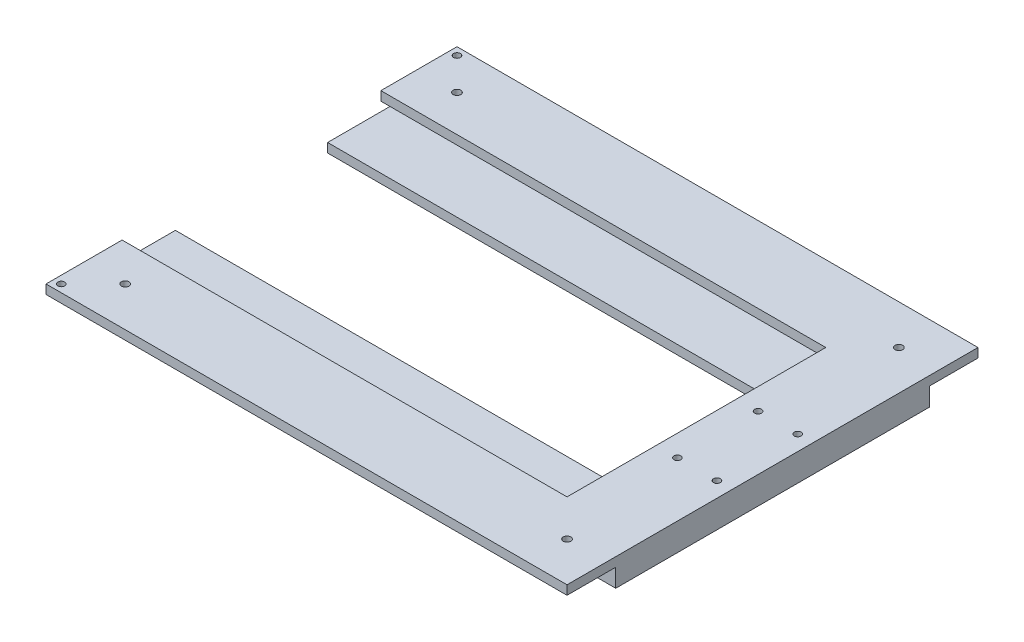
SolidWorks part; units mm, degrees
ref_plane "Спереди" through (0, 0, 0) normal (0, 0, 1) x (1, 0, 0)
ref_plane "Сверху" through (0, 0, 0) normal (0, 1, 0) x (1, 0, 0)
ref_plane "Справа" through (0, 0, 0) normal (1, 0, 0) x (0, 0, -1)
sketch "Эскиз1" plane through (0, 0, 0) normal (0, 1, 0) x (1, 0, 0)
  line L0 (50, -77.9215) -> (50, -347.9215)
  line L1 (-292.3, -77.9215) -> (50, -77.9215)
  line L2 (-292.3, -77.9215) -> (-292.3, -127.9215)
  line L3 (-292.3, -347.9215) -> (50, -347.9215)
  line L5 (-292.3, -127.9215) -> (0, -127.9215)
  line L7 (-292.3, -297.9215) -> (0, -297.9215)
  line L13 (-292.3, -297.9215) -> (-292.3, -347.9215)
  line L22 (0, -127.9215) -> (0, -297.9215)
  dimension "D1" = 342.3
  dimension "D12" = 50
  dimension "D2" = 270
  dimension "D3" = 50
  dimension "D4" = 50
  dimension "D9" = 50
  dimension "D8" = 77.9215
extrude "Бобышка-Вытянуть2" add sketch "Эскиз1" along normal blind 6
sketch "Эскиз2" plane through (0, 0, 0) normal (0, -1, 0) x (1, 0, 0)
  line L0 (-292.3, 127.9215) -> (0, 127.9215) construction
  line L5 (50, 347.9215) -> (50, 77.9215) construction
  line L6 (0, 297.9215) -> (-292.3, 297.9215) construction
  line L18 (50, 315.9215) -> (50, 109.9215)
  line L20 (6, 303.9215) -> (6, 121.9215)
  line L21 (-292.3, 77.9215) -> (-292.3, 127.9215) construction
  line L22 (50, 109.9215) -> (-292.3, 109.9215)
  line L24 (6, 121.9215) -> (-292.3, 121.9215)
  line L25 (-292.3, 109.9215) -> (-292.3, 121.9215)
  line L26 (-292.3, 297.9215) -> (-292.3, 347.9215) construction
  line L27 (50, 315.9215) -> (-292.3, 315.9215)
  line L29 (6, 303.9215) -> (-292.3, 303.9215)
  line L30 (-292.3, 315.9215) -> (-292.3, 303.9215)
  dimension "D1" = 44
  dimension "D2" = 12
  dimension "D3" = 12
  dimension "D4" = 6
  dimension "D5" = 6
extrude "Бобышка-Вытянуть3" add sketch "Эскиз2" along normal blind 6
sketch "Эскиз4" plane through (0, 6, 0) normal (0, 1, 0) x (1, 0, 0)
  line L0 (50, -77.9215) -> (-292.3, -77.9215) construction
  line L1 (-292.3, -77.9215) -> (-292.3, -127.9215) construction
  circle A0 centre (-266.3, -103.9215) radius 2.5
  dimension "D1" = 5
  dimension "D2" = 26
  dimension "D3" = 26
extrude "Вырез-Вытянуть1" cut sketch "Эскиз4" against normal through all
pattern_linear "Линейный массив2" count 2 spacing 290.3 along (1, 0, 0) count 2 spacing 218 along (0, 0, 1) of "Вырез-Вытянуть1"
sketch "Эскиз5" plane through (0, -6, 0) normal (0, -1, 0) x (1, 0, 0)
  line L8 (50, 315.9215) -> (-292.3, 315.9215)
  line L9 (-292.3, 315.9215) -> (-292.3, 262.9215)
  line L10 (-292.3, 262.9215) -> (0, 262.9215)
  line L11 (0, 262.9215) -> (0, 162.9215)
  line L12 (0, 162.9215) -> (-292.3, 162.9215)
  line L13 (-292.3, 162.9215) -> (-292.3, 109.9215)
  line L14 (-292.3, 109.9215) -> (50, 109.9215)
  line L15 (50, 109.9215) -> (50, 315.9215)
  point P0 (0, 212.9215)
  point P9 (50, 212.9215)
  dimension "D1" = 100
extrude "Бобышка-Вытянуть4" add sketch "Эскиз5" along normal blind 6
sketch "Эскиз6" plane through (0, -12, 0) normal (0, -1, 0) x (1, 0, 0)
  line L0 (40, 212.9215) -> (50, 212.9215) construction
  line L1 (40, 186.4215) -> (14, 186.4215) construction
  line L2 (40, 186.4215) -> (40, 239.4215) construction
  line L3 (40, 239.4215) -> (14, 239.4215) construction
  line L4 (14, 186.4215) -> (14, 239.4215) construction
  line L5 (50, 109.9215) -> (50, 315.9215) construction
  circle A1 centre (14, 239.4215) radius 2.25
  circle A2 centre (40, 239.4215) radius 2.25
  circle A3 centre (40, 186.4215) radius 2.25
  circle A4 centre (14, 186.4215) radius 2.25
  point P4 (50, 212.9215)
  point P6 (40, 212.9215)
  dimension "D4" = 4.5
  dimension "D1" = 53
  dimension "D2" = 26
  dimension "D3" = 10
extrude "Вырез-Вытянуть2" cut sketch "Эскиз6" against normal through all
sketch "Эскиз7" plane through (0, 0, 0) normal (0, -1, 0) x (1, 0, 0)
  line L0 (-292.3, 337.9215) -> (-282.3, 347.9215) construction
  line L1 (-292.3, 347.9215) -> (-282.3, 347.9215) construction
  line L2 (-292.3, 347.9215) -> (-292.3, 337.9215) construction
  line L3 (-292.3, 337.9215) -> (-282.3, 337.9215) construction
  line L4 (-282.3, 347.9215) -> (-282.3, 337.9215) construction
  line L5 (-292.3, 347.9215) -> (-282.3, 337.9215) construction
  line L6 (-282.3, 87.9215) -> (-292.3, 77.9215) construction
  line L7 (-292.3, 77.9215) -> (-282.3, 77.9215) construction
  line L8 (-292.3, 77.9215) -> (-292.3, 87.9215) construction
  line L9 (-292.3, 87.9215) -> (-282.3, 87.9215) construction
  line L10 (-282.3, 77.9215) -> (-282.3, 87.9215) construction
  line L11 (-292.3, 87.9215) -> (-282.3, 77.9215) construction
  circle A0 centre (-287.3, 342.9215) radius 2.25
  circle A1 centre (-287.3, 82.9215) radius 2.25
  point P12 (-287.3, 82.9215)
  dimension "D3" = 4.5
  dimension "D6" = 4.5
  dimension "D1" = 10
  dimension "D2" = 10
  dimension "D4" = 10
  dimension "D5" = 10
extrude "Вырез-Вытянуть3" cut sketch "Эскиз7" against normal through all
equation "\"Ширина груза\"= 160"
equation "\"Глубина груза\"= 240"
equation "\"Высота груза\"= 160"
equation "\"Ширина ячейки\"= \"Ширина груза\" + 10"
equation "\"Глубина ячейки\"= \"Глубина груза\" + 10"
equation "\"Высота ячейки\"= \"Высота груза\" + 10 + 13"
equation "\"Колво ячеек ширина\"= 2"
equation "\"Колво ячеек высота\"= 2"
equation "\"Толщина стенки\" = \"Толщина тонких панелей\""
equation "\"Крепление дверцы\"= 5 "
equation "\"Ширина рейки\"= \"Толщина шестерни\""
equation "\"Высота рейки\"= 20"
equation "\"Высота пола\" = 2*\"Толщина тонких панелей\""
equation "\"Колво полозьев\"= 5"
equation "\"Отступ рейки\"= 20"
equation "\"Глубина каретки\"= \"Глубина ячейки\" + 30 + \"Мотор Y высота корпуса\" + 20"
equation "\"Длинна рейки\" = (\"Ширина ячейки\"+\"Толщина вертикальных стенок\"+\"Крепление дверцы\")*\"Колво ячеек ширина\"+\"Ширина ячейки выгрузки\"*\"Колво выгрузки\"+\"Толщина вертикальных стенок\"+2*\"Отступ крепления мотора фиксации\"-\"Крепление дверцы\"*\"Колво ячеек ширина\""
equation "\"Отступ шпильки\"= 26"
equation "\"Диаметр шпильки\"= 5"
equation "\"Длинна шпильки\" = (\"Высота ячейки\"+\"Толщина горизонтальных плит\"+\"Высота пола\")*\"Колво ячеек высота\"+2*(\"Толщина горизонтальных плит\"+\"Отступ рейки\")"
equation "\"D2@Эскиз1\"=\"Ширина ячейки\" + \"Ширина пластины\" * 2 "
equation "\"D9@Эскиз1\"=\"Ширина пластины\""
equation "\"D3@Эскиз1\"=\"Ширина пластины\""
equation "\"D4@Эскиз1\"= \"Ширина пластины\""
equation "\"Ширина пластины\"= 50  "
equation "\"D1@Бобышка-Вытянуть2\"=\"Толщина стенки\""
equation "\"D1@Эскиз4\"= \"Диаметр шпильки\""
equation "\"D4@Линейный массив2\"=\"Ширина ячейки\" + \"Ширина пластины\" * 2  - \"Отступ шпильки\" * 2"
equation "\"D1@Эскиз1\"= \"Глубина каретки\""
equation "\"D3@Линейный массив2\"= \"Глубина каретки\" - \"Отступ шпильки\" * 2"
equation "\"D2@Эскиз4\"=\"Отступ шпильки\""
equation "\"D3@Эскиз4\"= \"Отступ шпильки\""
equation "\"D1@Эскиз2\"= \"Ширина пластины\" - \"Толщина стенки\""
equation "\"D2@Эскиз2\"=12"
equation "\"D4@Эскиз2\"= \"Толщина стенки\""
equation "\"D5@Эскиз2\"= \"Толщина стенки\""
equation "\"D1@Бобышка-Вытянуть4\"= \"Толщина стенки\""
equation "\"Вы\"=20"
equation "\"D1@Бобышка-Вытянуть3\"=6"
equation "\"Высота зона выгрузки\"= \"Высота ячейки\" * 2 + \"Толщина стенки\" * 2"
equation "\"Колво выгрузки\"= 1"
equation "\"Ширина ячейки выгрузки\" = \"Ширина ячейки\"+\"Толщина вертикальных стенок\"+2*\"Отступ крепления мотора фиксации\""
equation "\"Отступ крепления мотора фиксации\" = (\"Ширина пластины\"+20-\"Толщина вертикальных стенок\")/2"
equation "\"Мотор X ширина корпуса\"= 42.3"
equation "\"Мотор X высота корпуса\"= 42.3"
equation "\"Мотор X длина корпуса\"= 40"
equation "\"Мотор X вылет вала\"= 19.8"
equation "\"Мотор Y ширина корпуса\"= 42.3"
equation "\"Мотор Y высота корпуса\"= 42.3"
equation "\"Мотор Y длина корпуса\"= 48"
equation "\"Мотор Y вылет вала\"= 30"
equation "\"Мотор Z ширина корпуса\"= 42"
equation "\"Мотор Z высота корпуса\"= 42"
equation "\"Мотор Z длина корпуса\"= 40"
equation "\"Мотор Z вылет вала\"= 23"
equation "\"Мотор диаметр вала ПРЕДВ\"= 5"
equation "\"Мотор шаг крепления ПРЕДВ\"= 31"
equation "\"Мотор диаметр отверстий ПРЕДВ\"= 3"
equation "\"Мотор глубина отверстий ПРЕДВ\"= 4.5"
equation "\"Мотор диаметр буртика ПРЕДВ\"= 22"
equation "\"Мотор высота буртика ПРЕДВ\"= 2"
equation "\"Мотор диаметр шкива ПРЕДВ\"= 16"
equation "\"Мотор длина шкива ПРЕДВ\"= 12"
equation "\"Мотор отступ шкива ПРЕДВ\"= 5"
equation "\"Мотор X шаг градусов\"= 1.8"
equation "\"Мотор X ток А\"= 1.5"
equation "\"Мотор X сопротивление Ом\"= 1.3"
equation "\"Мотор X индуктивность мГн\"= 2"
equation "\"Мотор Y шаг градусов\"= 1.8"
equation "\"Мотор Y ток А\"= 2.2"
equation "\"Мотор Y сопротивление Ом\"= 0.9"
equation "\"Мотор Y индуктивность мГн\"= 2"
equation "\"Мотор Z шаг градусов\"= 1.8"
equation "\"Мотор Z ток А\"= 1"
equation "\"Мотор Z сопротивление Ом\"= 4"
equation "\"Мотор Z индуктивность мГн\"= 8"
equation "\"Мотор Y диаметр ротора\"= 25.78"
equation "\"Толщина тонких панелей\" = 6"
equation "\"Толщина вертикальных стенок\" = 6"
equation "\"Толщина горизонтальных плит\" = 6"
equation "\"Базовая высота корпуса\"= (\"Высота ячейки\"+\"Толщина тонких панелей\"+\"Высота пола\")*\"Колво ячеек высота\"+6*\"Толщина тонких панелей\"+\"Мотор X ширина корпуса\"+\"Мотор Y ширина корпуса\"+75"
equation "\"Высота корпуса\"= (\"Высота ячейки\"+\"Толщина горизонтальных плит\"+\"Высота пола\")*\"Колво ячеек высота\"+2*\"Толщина горизонтальных плит\"+4*\"Толщина тонких панелей\"+\"Мотор X ширина корпуса\"+\"Мотор Y ширина корпуса\"+75"
equation "\"Смещение центра корпуса\"= (\"Высота корпуса\"-\"Базовая высота корпуса\")/2-(\"Толщина горизонтальных плит\"-\"Толщина тонких панелей\")"
equation "\"Отметка пола\"= -\"Базовая высота корпуса\"/2+\"Толщина тонких панелей\""
equation "\"Отметка потолка\"= \"Отметка пола\"+\"Высота корпуса\"-2*\"Толщина горизонтальных плит\""
equation "\"Отметка верхней полки\"= \"Отметка потолка\"-(28+\"Толщина тонких панелей\")-\"Высота ячейки\"-\"Высота пола\""
equation "\"Отметка нижней полки\"= \"Отметка верхней полки\"-\"Высота ячейки\"-\"Высота пола\"-\"Толщина горизонтальных плит\""
equation "\"Толщина шестерни\"= 10"
